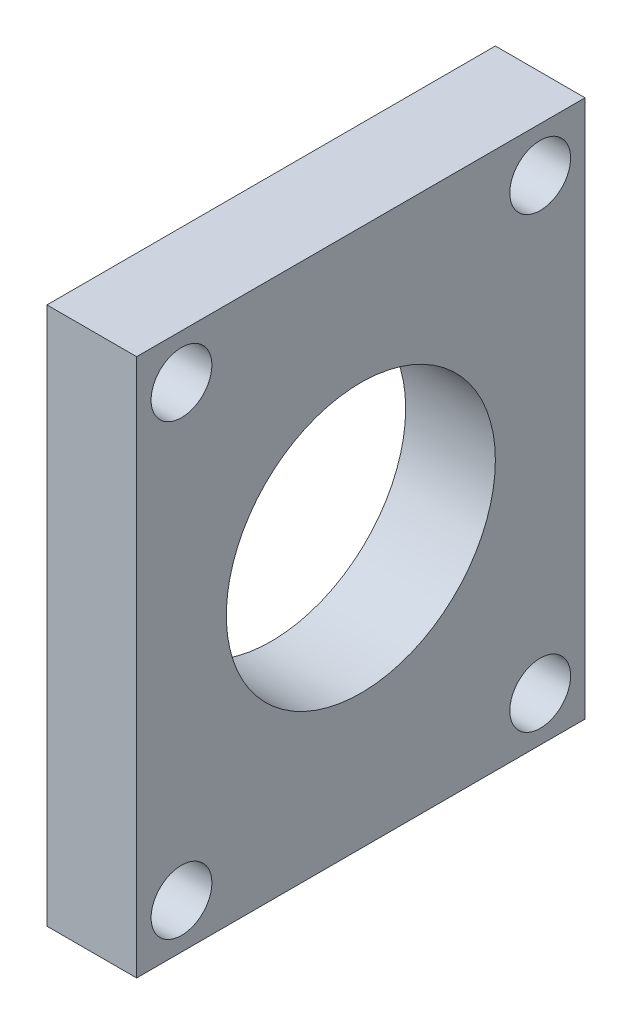
SolidWorks part; units mm, degrees
ref_plane "Front Plane" through (0, 0, 0) normal (0, 0, 1) x (1, 0, 0)
ref_plane "Top Plane" through (0, 0, 0) normal (0, 1, 0) x (1, 0, 0)
ref_plane "Right Plane" through (0, 0, 0) normal (1, 0, 0) x (0, 0, -1)
sketch "Sketch1" plane through (0, 0, 0) normal (1, 0, 0) x (0, 0, -1)
  line L1 (15.875, 0) -> (-15.875, 0)
  line L2 (15.875, 0) -> (15.875, 38.1)
  line L3 (15.875, 38.1) -> (-15.875, 38.1)
  line L4 (-15.875, 0) -> (-15.875, 38.1)
  dimension "D1" = 38.1
  dimension "D2" = 31.75
extrude "Boss-Extrude1" add sketch "Sketch1" along normal mid plane 6.35
sketch "Sketch2" plane through (3.175, 0, 0) normal (1, 0, 0) x (0, 0, -1)
  line L0 (-15.875, 0) -> (15.875, 0) construction
  line L1 (15.875, 38.1) -> (-15.875, 38.1) construction
  circle A0 centre (-12.7, 3.175) radius 2.1526
  circle A1 centre (-12.7, 34.925) radius 2.1526
  circle A2 centre (12.7, 3.175) radius 2.1526
  circle A3 centre (12.7, 34.925) radius 2.1526
  point P10 (0, 0)
  point P11 (0, 0)
  point P13 (0, 0)
  point P16 (12.7, 7.0889)
  dimension "D4" = 4.3053
  dimension "D1" = 12.7
  dimension "D2" = 12.7
  dimension "D3" = 3.175
  dimension "D5" = 3.175
extrude "Cut-Extrude1" cut sketch "Sketch2" against normal through all
sketch "Sketch3" plane through (3.175, 0, 0) normal (1, 0, 0) x (0, 0, -1)
  line L0 (0, 3.4925) -> (0, -3.4925) construction
  line L1 (-15.875, 0) -> (15.875, 0) construction
  circle A0 centre (0, 19.05) radius 9.525
  dimension "D1" = 19.05
  dimension "D2" = 19.05
extrude "Cut-Extrude2" cut sketch "Sketch3" against normal through all
